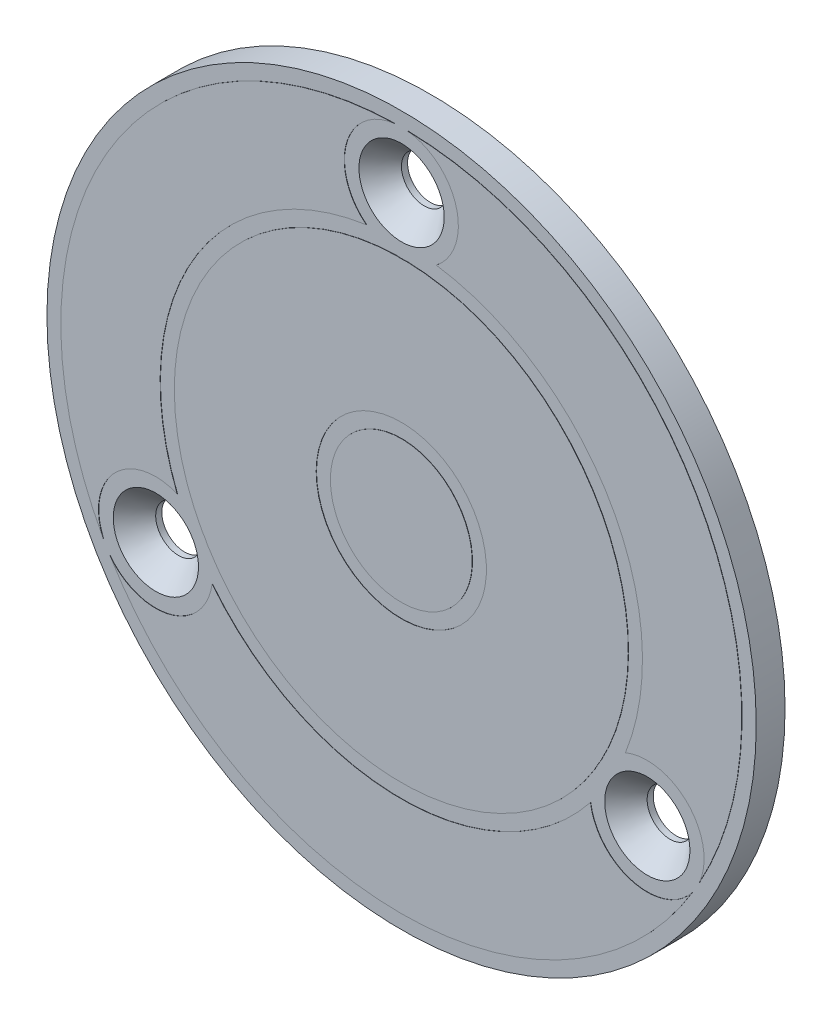
SolidWorks part; units mm, degrees
ref_plane "Front Plane" through (0, 0, 0) normal (0, 0, 1) x (1, 0, 0)
ref_plane "Top Plane" through (0, 0, 0) normal (0, 1, 0) x (1, 0, 0)
ref_plane "Right Plane" through (0, 0, 0) normal (1, 0, 0) x (0, 0, -1)
sketch "Sketch1" plane through (0, 0, 0) normal (0, 0, 1) x (1, 0, 0)
  circle A0 centre (0, 0) radius 12.5
  dimension "D1" = 25
extrude "Extrude1" add sketch "Sketch1" along normal blind 1.016
sketch "Sketch2" plane through (0, 0, 1.016) normal (0, 0, 1) x (1, 0, 0)
  circle A0 centre (0, 0) radius 2.5
  circle A1 centre (0, 0) radius 3
  circle A2 centre (0, 0) radius 8
  circle A3 centre (0, 0) radius 8.5
  circle A4 centre (0, 0) radius 12
  circle A5 centre (0, 0) radius 12.5 construction
  dimension "D1" = 0.5
  dimension "D2" = 0.5
  dimension "D3" = 0.5
  dimension "D4" = 5
  dimension "D5" = 5
  dimension "D6" = 3.5
extrude "Extrude2" add sketch "Sketch2" along normal blind 0.01 contours A4 A3 | A2 A1 | A0
sketch "Sketch3" plane through (0, 0, 1.026) normal (0, 0, 1) x (1, 0, 0)
  point P0 (0, 10)
  dimension "D1" = 10
hole_wizard "CSK for #0 Flat Head Machine Screw1" positions "3DSketch1" profile "Sketch4" countersink size "#0" standard "Ansi Inch" end condition through all
sketch3d "3DSketch1"
  point P0 (0, 10, 1.026)
sketch "Sketch4" plane through (0, 10, 1.026) normal (1, 0, 0) x (0, -1, 0)
  line L0 (0, 0) -> (0, 1.026)
  line L1 (0, 1.026) -> (0.8064, 1.026)
  line L2 (0.8064, 1.026) -> (0.8065, 0.8108)
  line L3 (0.8065, 0.8108) -> (1.5113, 0)
  line L5 (1.5113, 0) -> (0, 0)
  line L6 (-0.8065, 0.8108) -> (-1.5113, 0) construction
  line L11 (0, -6.35) -> (0, 107.95) construction
  dimension "Thru Hole Dia." = 1.6129
  dimension "Thru Hole Depth" = 1.026
  dimension "Near C'Sink Dia." = 3.0226
  dimension "Near C'Sink Angle" = 82
pattern_circular "CirPattern1" count 3 over 360 about axis through (0, 0, 0) along (0, 0, 1) of "CSK for #0 Flat Head Machine Screw1"
sketch "Sketch5" [suppressed] plane through (0, 0, 1.5975) normal (0, 0, 1) x (1, 0, 0)
  line L0 (7.5, 0) -> (14.5, 0) construction
  line L1 (15, 0) -> (12.5, 0) construction
  circle A0 centre (0, 0) radius 0.5
  circle A1 centre (11, 0) radius 0.5
  circle A2 centre (13.75, 0) radius 0.5
  circle A3 centre (0, 0) radius 7.5 construction
  circle A4 centre (0, 0) radius 7.5 construction
  circle A5 centre (0, 0) radius 14.5 construction
  circle A6 centre (0, 0) radius 15 construction
  circle A7 centre (0, 0) radius 15 construction
  circle A8 centre (0, 0) radius 12.5 construction
  point P26 (13.75, 0)
  point P27 (11, 0)
  dimension "D1" = 1
extrude "Extrude3" [suppressed] cut sketch "Sketch5" against normal through all
sketch "Sketch6" plane through (0, 0, 1.026) normal (0, 0, 1) x (1, 0, 0)
  circle A0 centre (0, 10) radius 2.0113
  circle A1 centre (-8.6603, -5) radius 2.0113
  circle A2 centre (8.6603, -5) radius 2.0113
  arc A3 (0.1701, 8.4983) -> (-0.1701, 8.4983) centre (0, 10) ccw construction
  dimension "D1" = 0.5
extrude "Extrude5" cut sketch "Sketch6" against normal up to surface (0.01 mm away) up to face at (0, 0, 1.016)
